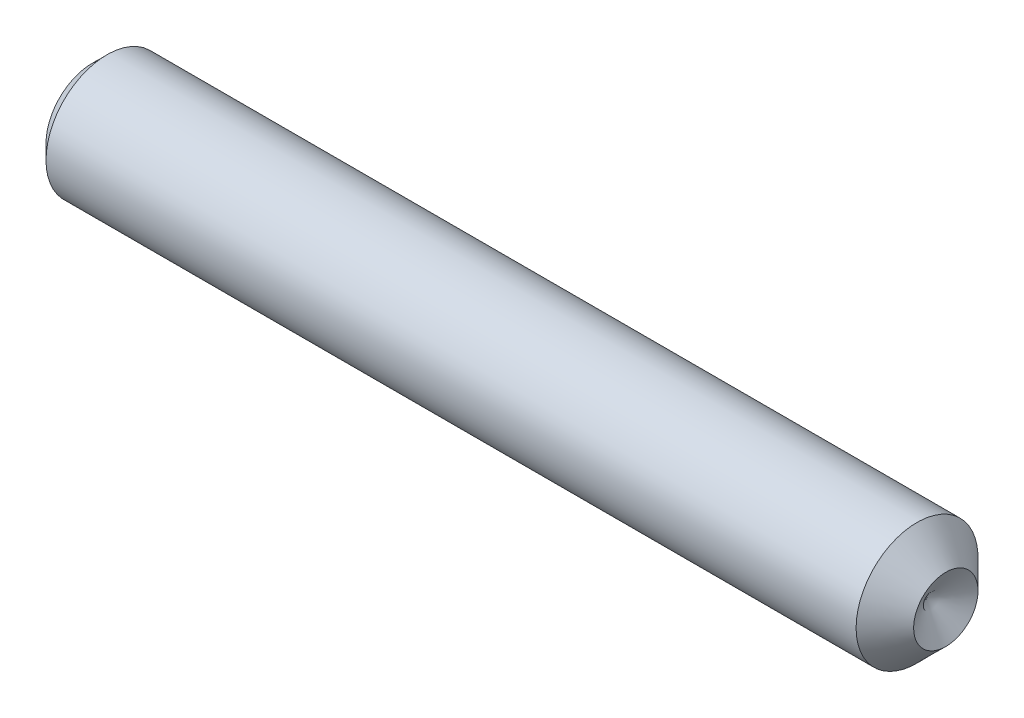
SolidWorks part; units mm, degrees
ref_plane "Plane1" through (0, 0, 0) normal (0, 0, 1) x (1, 0, 0)
ref_plane "Plane2" through (0, 0, 0) normal (0, 1, 0) x (1, 0, 0)
ref_plane "Plane3" through (0, 0, 0) normal (1, 0, 0) x (0, 0, -1)
sketch "BodySke" plane through (0, 0, 0) normal (0, 0, 1) x (1, 0, 0)
  line L0 (0, 0) -> (0, 2.4194)
  line L1 (0, 2.4194) -> (0.7557, 3.175)
  line L2 (0.7557, 3.175) -> (42.9514, 3.175)
  line L3 (42.9514, 3.175) -> (44.45, 1.6764)
  line L4 (43.4427, 0) -> (0, 0)
  line L5 (-12.7, 0) -> (88.9, 0) construction
  line L6 (43.4427, 0) -> (44.45, 1.6764)
  line L7 (44.45, 1.6764) -> (44.45, 11.2014) construction
  line L8 (0, -2.4193) -> (0.7557, -3.175) construction
  line L9 (43.4427, 0) -> (44.45, -1.6764) construction
  line L10 (42.9514, -3.175) -> (44.45, -1.6764) construction
  line L11 (1.27, 15.875) -> (1.27, -3.175) construction
  dimension "Length" = 44.45
  dimension "Diameter" = 6.35
  dimension "Drive_ch_ang" = 45
  dimension "Minor_dia" = 4.8387
  dimension "Cup_nose_ang" = 45
  dimension "Cup_ang" = 118
  dimension "Cup_dia" = 3.3528
  dimension "Advance" = 1.27
revolve "BaseBody" add sketch "BodySke" angle 360 about L5
cosmetic thread "ThreadCosmetic" [suppressed] parameters "Thread_minor"=4.8387
sketch "Sketch2" plane through (0, 0, 0) normal (-1, 0, 0) x (0, 0, 1)
  line L0 (0.9165, 1.5875) -> (-0.9165, 1.5875)
  line L1 (-0.9165, 1.5875) -> (-1.8331, 0)
  line L2 (0.9165, 1.5875) -> (1.8331, 0)
  line L3 (0.9165, -1.5875) -> (1.8331, 0)
  line L4 (0.9165, -1.5875) -> (-0.9165, -1.5875)
  line L5 (-0.9165, -1.5875) -> (-1.8331, 0)
  dimension "Hex_size" = 3.175
  dimension "D2" = 1.5875
  dimension "D3" = 1.5875
extrude "Hex" cut sketch "Sketch2" against normal blind 3.175
sketch "Sketch4" plane through (0, 4.7709, -0.5249) normal (-1, 0, 0) x (0, 0, 1)
  line L0 (0.5249, -4.7709) -> (2.4172, -4.7709)
  line L1 (0.5249, -4.7709) -> (6.6732, -1.2211) construction
  line L2 (0.5249, -4.7709) -> (1.471, -3.1321)
  line L3 (2.0912, -4.3358) -> (2.3286, -4.1988)
  line L4 (1.6848, -3.6319) -> (1.9222, -3.4948)
  arc A0 (2.0912, -4.3358) -> (1.6848, -3.6319) centre (0.5249, -4.7709) ccw
  arc A1 (2.4172, -4.7709) -> (2.3286, -4.1988) centre (0.5249, -4.7709) ccw
  arc A2 (1.471, -3.1321) -> (1.9222, -3.4948) centre (0.5249, -4.7709) cw
  circle A3 centre (0.5249, -4.7709) radius 1.6256 construction
  circle A4 centre (0.5249, -4.7709) radius 1.8923 construction
  dimension "D1" = 30
  dimension "Spline_n_dim" = 3.2512
  dimension "Spline_m_dim" = 3.7846
  dimension "Spline_a_dim" = 60
  dimension "D3" = 0.4064
  dimension "Spline_p_dim" = 0.8128
extrude "Spline" [suppressed] cut sketch "Sketch4" against normal blind 3.175
pattern_circular "CirPattern1" [suppressed] count 6 every 60 about axis through (-12.7, 0, 0) along (1, 0, 0)
sketch "ThdSchSke" plane through (0, 0, 0) normal (0, 0, 1) x (1, 0, 0)
  line L0 (0.7557, -2.4193) -> (0.2265, -3.175)
  line L1 (0.7557, -2.4193) -> (1.2848, -3.175)
  line L2 (1.2848, -3.175) -> (1.2848, -3.9688)
  line L3 (-3.175, 0) -> (5.1513, 0) construction
  line L4 (0.7557, 3.175) -> (0.7557, -3.175) construction
  line L5 (1.2848, -3.9688) -> (0.2265, -3.9688)
  line L6 (0.2265, -3.9688) -> (0.2265, -3.175)
  dimension "Thread_minor" = 4.8387
  dimension "Diameter" = 6.35
  dimension "SideAngle" = 55
  dimension "VeeAngle" = 70
  dimension "Overcut" = 7.9375
revolve "ThreadSchematic" [suppressed] cut sketch "ThdSchSke" angle 360 about L3
pattern_linear "ThdSchPat" [suppressed]
equation "\"D2@Sketch2\" = \"Hex_size@Sketch2\" / 2"
equation "\"D3@Sketch2\" = \"Hex_size@Sketch2\" / 2"
equation "\"Thread_minor@ThreadCosmetic\" = \"Minor_dia@BodySke\""
equation "\"D1@Sketch4\" = \"Spline_a_dim@Sketch4\" / 2"
equation "\"D3@Sketch4\" = \"Spline_p_dim@Sketch4\" / 2"
equation "\"D2@CirPattern1\" = \"Spline_a_dim@Sketch4\""
equation "\"Num_teeth@CirPattern1\" = 360 / \"D2@CirPattern1\""
equation "\"Thread_minor@ThdSchSke\" = \"Thread_minor@ThreadCosmetic\""
equation "\"Diameter@ThdSchSke\" = \"Diameter@BodySke\""
equation "\"Overcut@ThdSchSke\" = \"Diameter@BodySke\" * 1.25"
equation "\"Num_threads@ThdSchPat\" = int( (\"Length@BodySke\" - ( ( ( \"Diameter@BodySke\" - \"Minor_dia@BodySke\" ) * 0.5 ) / tan( \"Drive_ch_ang@BodySke\" * 0.017453292 ) ) - ( ( ( \"Diameter@BodySke\" - \"Cup_dia@BodySke\" ) * 0.5 ) * tan( \"Cup_nose_ang@BodySke\" * 0.017453292 ) ) ) / \"Advance@BodySke\" + 0.999 )  + 1"
equation "\"Advance@ThdSchPat\" = (\"Length@BodySke\" - ( ( ( \"Diameter@BodySke\" - \"Minor_dia@BodySke\" ) * 0.5 ) / tan( \"Drive_ch_ang@BodySke\" * 0.017453292 ) ) - ( ( ( \"Diameter@BodySke\" - \"Cup_dia@BodySke\" ) * 0.5 ) * tan( \"Cup_nose_ang@BodySke\" * 0.017453292 ) ) ) /  (\"Num_threads@ThdSchPat\" - 1) 'relax it"
equation "' \"Num_threads@ThdSchPat\" = \"Num_threads@ThdSchPat\" - sgn( \"Num_threads@ThdSchPat\" - 1) '---chamfered tips only---"
